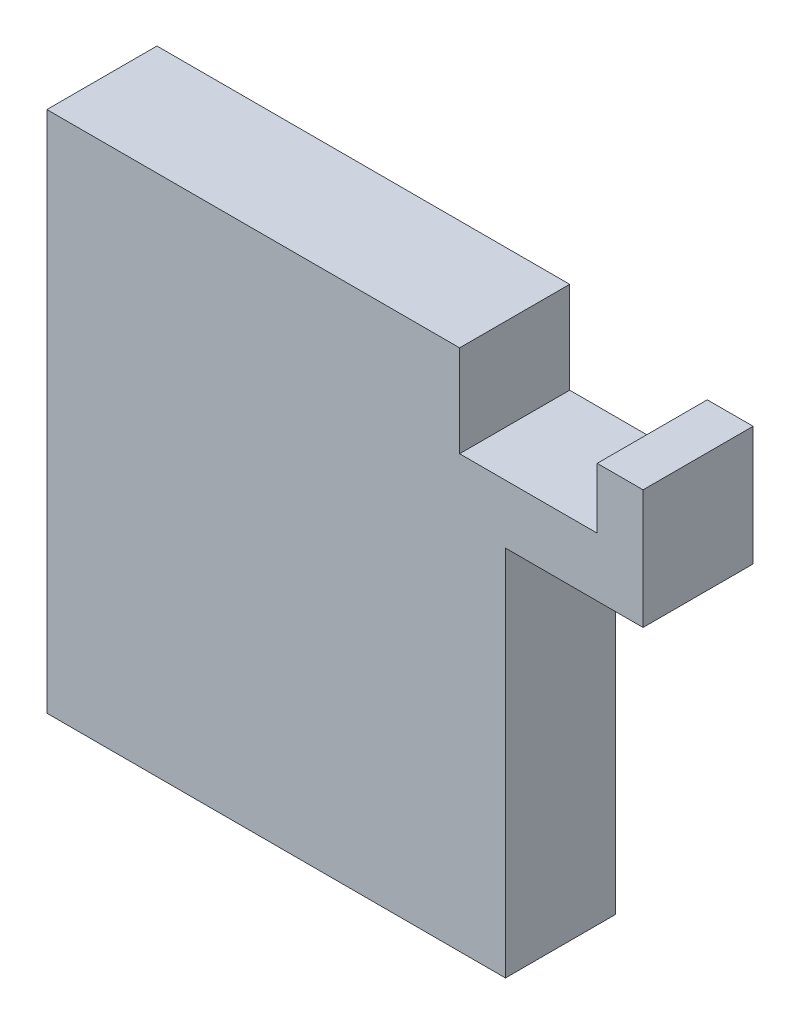
SolidWorks part; units mm, degrees
ref_plane "前视基准面" through (0, 0, 0) normal (0, 0, 1) x (1, 0, 0)
ref_plane "上视基准面" through (0, 0, 0) normal (0, 1, 0) x (1, 0, 0)
ref_plane "右视基准面" through (0, 0, 0) normal (1, 0, 0) x (0, 0, -1)
sketch "草图1" plane through (0, 0, 0) normal (0, 0, 1) x (1, 0, 0)
  line L0 (4.2193, 10.5) -> (4.2193, 4.8)
  line L1 (4.2193, 10.5) -> (8.7193, 10.5)
  line L2 (8.7193, 10.5) -> (8.7193, 9.5)
  line L3 (8.7193, 9.5) -> (10.2193, 9.5)
  line L4 (10.2193, 9.5) -> (10.2193, 10.1595)
  line L5 (10.2193, 10.1595) -> (10.7193, 10.1595)
  line L6 (10.7193, 10.1595) -> (10.7193, 8.8595)
  line L7 (9.2193, 4.8) -> (4.2193, 4.8)
  line L10 (10.7193, 8.8595) -> (9.2193, 8.8595)
  line L11 (9.2193, 8.8595) -> (9.2193, 4.8)
  line L12 (9.4, -1) -> (9.1, -1) construction
  line L13 (10.2193, 9.5) -> (10.2193, 8.8595) construction
  line L14 (10.4, 7.8) -> (-18.1, 7.8) construction
  point P14 (9.25, -1)
  dimension "D1" = 1.3
  dimension "D2" = 0.5
  dimension "D3" = 1.5
  dimension "D4" = 10.5
  dimension "D5" = 5
  dimension "D6" = 1
  dimension "D7" = 3
  dimension "D8" = 1
extrude "凸台-拉伸1" add sketch "草图1" along normal blind 1.2 contours L1 L2 L3 L4 L5 L6 L10 L11 L7 L0
